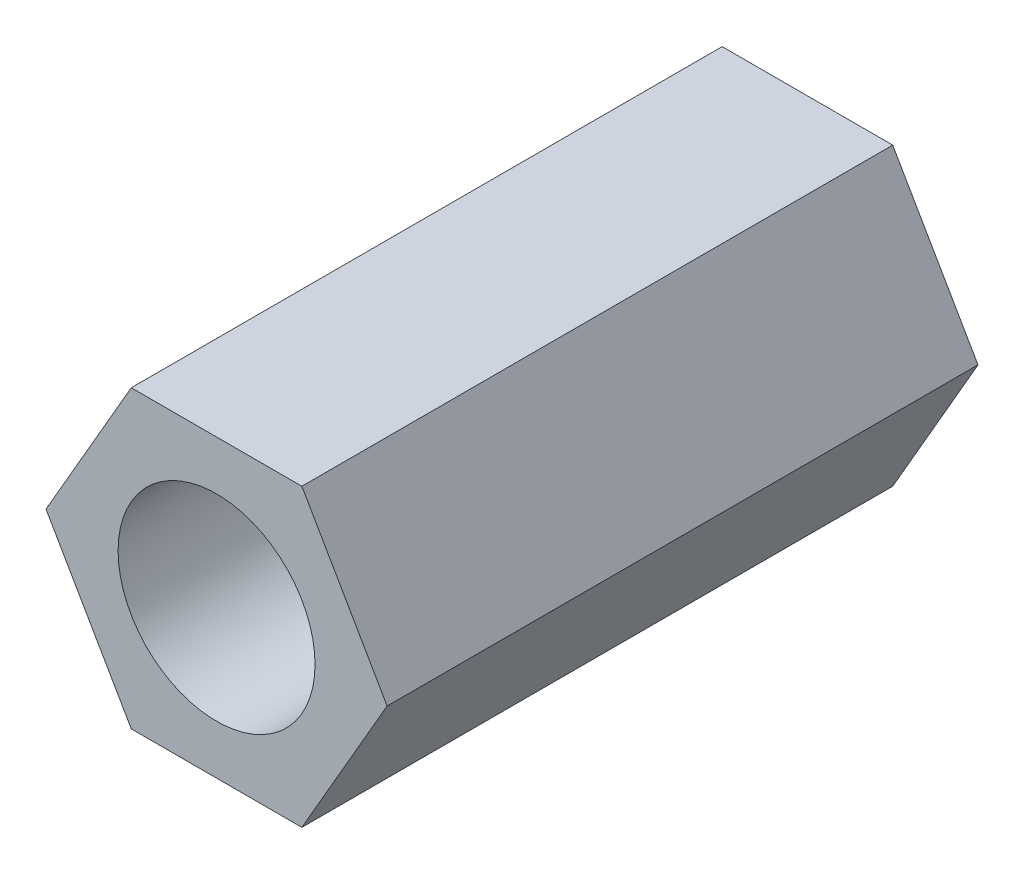
SolidWorks part; units mm, degrees
ref_plane "前视基准面" through (0, 0, 0) normal (0, 0, 1) x (1, 0, 0)
ref_plane "上视基准面" through (0, 0, 0) normal (0, 1, 0) x (1, 0, 0)
ref_plane "右视基准面" through (0, 0, 0) normal (1, 0, 0) x (0, 0, -1)
sketch "草图1" plane through (0, 0, 0) normal (0, 0, 1) x (1, 0, 0)
  line L1 (1.7321, 0) -> (0.866, 1.5)
  line L2 (0.866, 1.5) -> (-0.866, 1.5)
  line L3 (-0.866, 1.5) -> (-1.7321, 0)
  line L4 (-1.7321, 0) -> (-0.866, -1.5)
  line L5 (-0.866, -1.5) -> (0.866, -1.5)
  line L6 (0.866, -1.5) -> (1.7321, 0)
  circle A0 centre (0, 0) radius 1
  circle A1 centre (0, 0) radius 1.5 construction
  dimension "D1" = 2
  dimension "D2" = 3
extrude "凸台-拉伸1" add sketch "草图1" along normal blind 6
